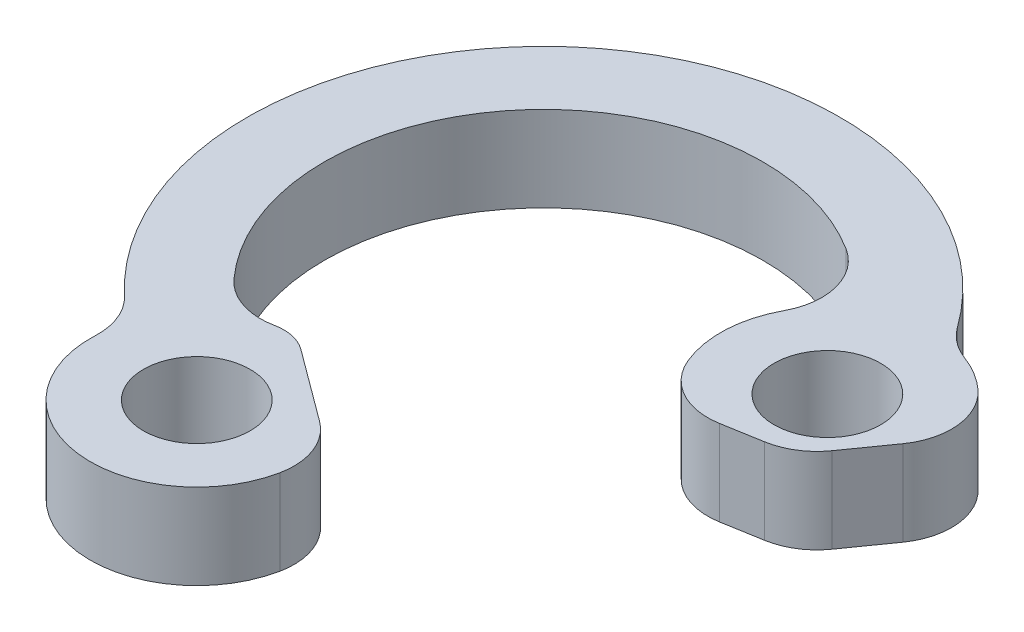
SolidWorks part; units mm, degrees
ref_plane "Front Plane" through (0, 0, 0) normal (0, 0, 1) x (1, 0, 0)
ref_plane "Top Plane" through (0, 0, 0) normal (0, 1, 0) x (1, 0, 0)
ref_plane "Right Plane" through (0, 0, 0) normal (1, 0, 0) x (0, 0, -1)
sketch "Sketch2" plane through (0, 0, 0) normal (0, 1, 0) x (1, 0, 0)
  circle A3 centre (87.0735, 81.0463) radius 2.5
  circle A5 centre (72.5387, 66.0204) radius 2.5
  arc A9 (84.158, 85.1082) -> (87.9596, 85.9672) centre (87.0735, 81.0463) ccw
  arc A10 (67.7859, 67.5732) -> (70.0824, 70.3755) centre (72.5387, 66.0204) ccw
  arc A16 (84.158, 85.1082) -> (70.0824, 70.3755) centre (76.1332, 78.6848) ccw
  arc A18 (87.9715, 85.965) -> (67.7859, 67.5732) centre (76.1332, 78.6848) ccw
extrude "Boss-Extrude1" add sketch "Sketch2" along normal blind 4
fillet "Fillet1" radius 3 4 edges at (67.7859, 2, -67.5732) (70.0824, 2, -70.3755) (84.158, 2, -85.1082) (87.9715, 2, -85.965)
sketch "Sketch4" plane through (0, 0, 0) normal (0, -1, 0) x (-1, 0, 0)
  line L0 (-78.0637, 66.7167) -> (-72.145, 71.0915)
  line L1 (-72.145, 71.0915) -> (-73.0772, 72.3527)
  line L2 (-73.0772, 72.3527) -> (-78.9959, 67.9779)
  line L3 (-78.9959, 67.9779) -> (-78.0637, 66.7167)
extrude "Cut-Extrude2" cut sketch "Sketch4" against normal blind 7
fillet "Fillet2" radius 3 1 edges at (77.3948, 2, -67.211)
fillet "Fillet3" radius 2 1 edges at (72.2523, 2, -71.0122)
sketch "Sketch5" plane through (0, 4, 0) normal (0, 1, 0) x (1, 0, 0)
  line L0 (91.9157, 82.2928) -> (87.5095, 76.0653)
  line L1 (91.9157, 82.2928) -> (94.0459, 81.0848)
  line L2 (94.0459, 81.0848) -> (89.2486, 74.6155)
  line L3 (89.2486, 74.6155) -> (87.5095, 76.0653)
  arc A0 (82.6696, 83.4139) -> (88.8113, 85.7346) centre (87.0735, 81.0463) ccw construction
extrude "Cut-Extrude3" cut sketch "Sketch5" against normal blind 4
fillet "Fillet4" radius 3 2 edges at (87.5095, 2, -76.0653) (91.9157, 2, -82.2928)
sketch "Sketch6" plane through (0, 4, 0) normal (0, 1, 0) x (1, 0, 0)
  line L0 (88.77, 77.8469) -> (84.083, 77.0392)
  line L1 (90.8599, 80.8006) -> (88.5653, 77.5575) construction
  line L2 (84.083, 77.0392) -> (84.6593, 75.3461)
  line L3 (84.6593, 75.3461) -> (89.0906, 75.9868)
  line L4 (89.0906, 75.9868) -> (88.77, 77.8469)
  arc A0 (82.6696, 83.4139) -> (84.6804, 76.6562) centre (87.0735, 81.0463) ccw construction
extrude "Cut-Extrude4" cut sketch "Sketch6" against normal blind 5
fillet "Fillet5" radius 3 2 edges at (84.083, 2, -77.0392) (88.77, 2, -77.8469)
